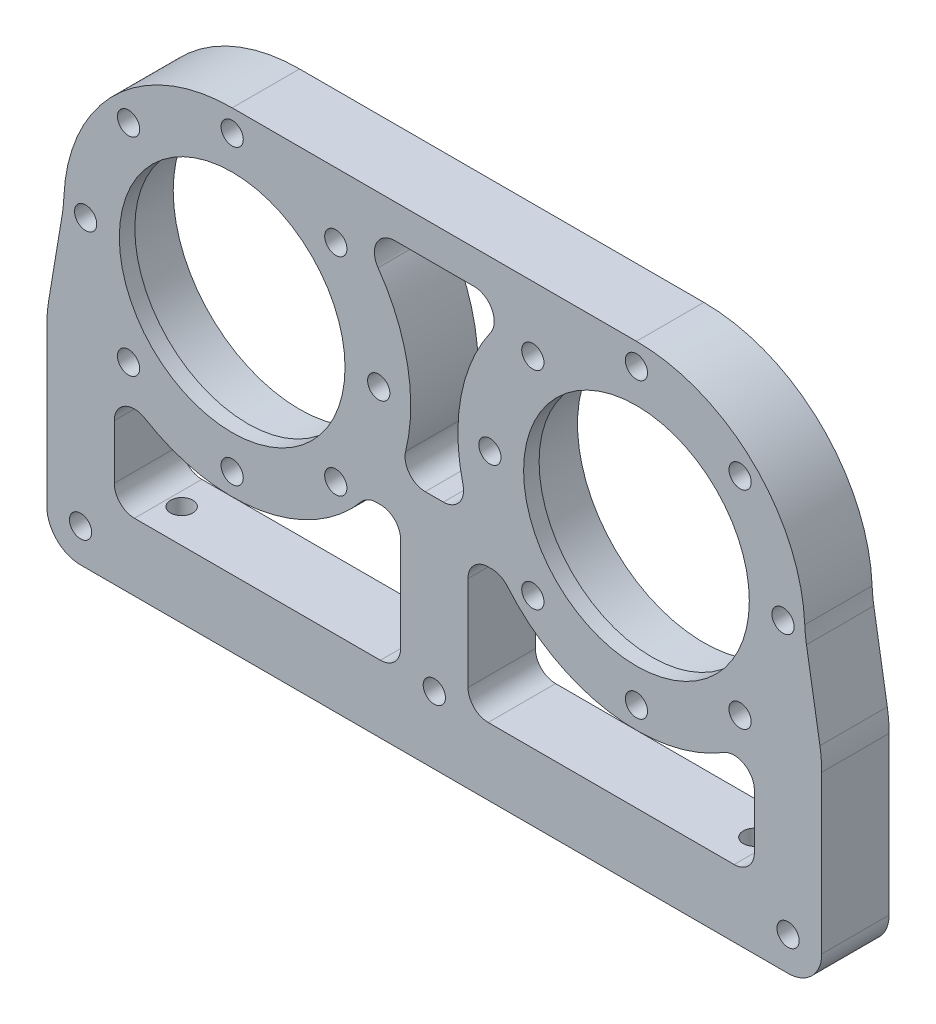
SolidWorks part; units mm, degrees
material "5052-H34"
ref_plane "正面" through (0, 0, 0) normal (0, 0, 1) x (1, 0, 0)
ref_plane "平面" through (0, 0, 0) normal (0, 1, 0) x (1, 0, 0)
ref_plane "右側面" through (0, 0, 0) normal (1, 0, 0) x (0, 0, -1)
sketch "ｽｹｯﾁ1" plane through (0, 0, 0) normal (0, 0, 1) x (1, 0, 0)
  line L0 (-57.5, 15) -> (-2.5, 15) construction
  line L1 (57.5, 15) -> (-57.5, 15)
  line L2 (57.5, 15) -> (57.5, -15)
  line L3 (57.5, -15) -> (-57.5, -15)
  line L4 (-57.5, 15) -> (-57.5, -15)
  line L5 (57.5, 15) -> (-57.5, -15) construction
  line L6 (57.5, -15) -> (-57.5, 15) construction
  line L7 (0, 15) -> (0, -15) construction
  line L8 (-57.5, 0) -> (57.5, 0) construction
  line L9 (-30, -15) -> (-30, 30) construction
  line L10 (-55, 30) -> (-57.5, 15)
  line L11 (-30, 55) -> (30, 55)
  line L12 (55, 30) -> (57.5, 15)
  circle A0 centre (-30, 30) radius 25
  circle A1 centre (30, 30) radius 25
  point P0 (0, 0)
  point P11 (2.5, 15)
  dimension "D4" = 50
  dimension "D1" = 115
  dimension "D2" = 30
  dimension "D3" = 55
  dimension "D5" = 45
  dimension "D6" = 27.5
extrude "ﾎﾞｽ - 押し出し1" add sketch "ｽｹｯﾁ1" along normal blind 10 contours L1 A1 A0 L4 L3 L2 | A0 L1 | L1 A1 L11 A0 | A1 L1 | A1 L1 | L1 A0 | L12 A1 L1 | A0 L10 L1
fillet "ﾌｨﾚｯﾄ1" radius 20 4 edges at (-57.5, 15, 5) (-55, 30, 5) (55, 30, 5) (57.5, 15, 5)
sketch "ｽｹｯﾁ2" plane through (0, 0, 10) normal (0, 0, 1) x (1, 0, 0)
  line L0 (0, 0) -> (0, 55) construction
  line L1 (-30, 55) -> (30, 55) construction
  line L2 (30, 30) -> (30, -15) construction
  line L3 (57.5, -15) -> (-57.5, -15) construction
  circle A0 centre (30, 30) radius 18.75
  circle A1 centre (-30, 30) radius 18.75
  dimension "D1" = 37.5
extrude "ｶｯﾄ - 押し出し1" cut sketch "ｽｹｯﾁ2" against normal through all
sketch "ｽｹｯﾁ4" plane through (0, 0, 0) normal (0, 0, -1) x (-1, 0, 0)
  line L0 (-57.5, -15) -> (57.5, -15) construction
  line L1 (-47.5, 15) -> (47.5, 15)
  line L2 (-47.5, 15) -> (-47.5, -5)
  line L3 (-47.5, -5) -> (47.5, -5)
  line L4 (47.5, 15) -> (47.5, -5)
  line L5 (-57.5, 13.3447) -> (-57.5, -15) construction
  line L6 (57.5, 13.3447) -> (57.5, -15) construction
  line L7 (0, 15) -> (0, -5) construction
  line L9 (-5, 15) -> (5, 15)
  line L10 (-5, 15) -> (-5, -5)
  line L11 (-5, -5) -> (5, -5)
  line L12 (5, 15) -> (5, -5)
  circle A0 centre (-30, 30) radius 25
  circle A1 centre (30, 30) radius 25
  dimension "D5" = 50
  dimension "D1" = 10
  dimension "D2" = 10
  dimension "D3" = 10
  dimension "D4" = 20
  dimension "D6" = 5
  dimension "D7" = 5
extrude "ｶｯﾄ - 押し出し3" cut sketch "ｽｹｯﾁ4" against normal through all contours A0 L1 L2 L3 L10 | L1 A1 L12 L3 L4
fillet "ﾌｨﾚｯﾄ3" radius 3 10 edges at (10, 15, 5) (5, 15, 5) (5, -5, 5) (47.5, -5, 5) (-47.5, -5, 5) (-5, -5, 5) (-5, 15, 5) (-10, 15, 5) (-47.5, 12.1464, 5) (47.5, 12.1464, 5)
sketch "ｽｹｯﾁ5" plane through (0, 0, 0) normal (0, 0, -1) x (-1, 0, 0)
  line L0 (0, 0) -> (0, 55) construction
  line L1 (30, 55) -> (-30, 55) construction
  line L2 (-30, 48.75) -> (-30, 11.25) construction
  circle A0 centre (-30, 30) radius 21.75 construction
  circle A1 centre (-30, 51.75) radius 1.65
  circle A2 centre (-14.6204, 45.3796) radius 1.65
  circle A3 centre (-8.25, 30) radius 1.65
  circle A4 centre (-14.6204, 14.6204) radius 1.65
  circle A5 centre (-30, 8.25) radius 1.65
  circle A6 centre (-45.3796, 14.6204) radius 1.65
  circle A7 centre (-51.75, 30) radius 1.65
  circle A8 centre (-45.3796, 45.3796) radius 1.65
  circle A9 centre (30, 30) radius 21.75 construction
  circle A10 centre (45.3796, 45.3796) radius 1.65
  circle A11 centre (51.75, 30) radius 1.65
  circle A12 centre (45.3796, 14.6204) radius 1.65
  circle A13 centre (30, 8.25) radius 1.65
  circle A14 centre (14.6204, 14.6204) radius 1.65
  circle A15 centre (8.25, 30) radius 1.65
  circle A16 centre (14.6204, 45.3796) radius 1.65
  circle A17 centre (30, 51.75) radius 1.65
  circle A18 centre (-30, 30) radius 18.75 construction
  point P22 (-30, 30)
  point P43 (30, 30)
  dimension "D1" = 43.5
  dimension "D2" = 3.3
  dimension "D3" = 8
extrude "ｶｯﾄ - 押し出し4" cut sketch "ｽｹｯﾁ5" against normal through all
sketch "ｽｹｯﾁ6" plane through (0, 0, 0) normal (0, 0, -1) x (-1, 0, 0)
  line L0 (-57.5, -15) -> (57.5, -15) construction
  line L1 (-57.5, 13.3447) -> (-57.5, -15) construction
  line L2 (0, 0) -> (0, -15) construction
  circle A0 centre (-52.5, -10) radius 1.65
  circle A1 centre (52.5, -10) radius 1.65
  circle A2 centre (0, -5) radius 1.65
  dimension "D1" = 3.3
  dimension "D2" = 5
  dimension "D3" = 5
  dimension "D4" = 10
  dimension "D5" = 3.3
extrude "ｶｯﾄ - 押し出し5" cut sketch "ｽｹｯﾁ6" against normal through all
fillet "ﾌｨﾚｯﾄ5" radius 5 2 edges at (-57.5, -15, 5) (57.5, -15, 5)
sketch "ｽｹｯﾁ7" plane through (0, 0, 10) normal (0, 0, 1) x (1, 0, 0)
  circle A0 centre (-30, 30) radius 18.75
  circle A1 centre (30, 30) radius 18.75
  circle A2 centre (-30, 30) radius 16.75
  circle A3 centre (30, 30) radius 16.75
  dimension "D1" = 37.5
  dimension "D2" = 37.5
  dimension "D3" = 33.5
  dimension "D4" = 33.5
extrude "ﾎﾞｽ - 押し出し2" add sketch "ｽｹｯﾁ7" against normal blind 2.3
sketch "ｽｹｯﾁ8" plane through (0, 0, 0) normal (0, 0, -1) x (-1, 0, 0)
  line L0 (0, 0) -> (0, 55) construction
  line L1 (30, 55) -> (-30, 55) construction
  line L2 (-12.6147, 50) -> (12.6147, 50)
  line L3 (-5.4592, 20) -> (5.4592, 20)
  line L4 (-52.5, -15) -> (52.5, -15) construction
  circle A0 centre (-30, 30) radius 26.5
  circle A1 centre (30, 30) radius 26.5
  point P15 (0, 20)
  point P16 (0, 50)
  dimension "D1" = 53
  dimension "D2" = 5
  dimension "D3" = 35
extrude "ｶｯﾄ - 押し出し6" cut sketch "ｽｹｯﾁ8" against normal blind 10 contours L3 L0 L2 A0 | L0 L3 A1 L2
fillet "ﾌｨﾚｯﾄ6" radius 3 4 edges at (-5.4592, 20, 5) (5.4592, 20, 5) (-12.6147, 50, 5) (12.6147, 50, 5)
sketch "ｽｹｯﾁ9" plane through (0, -15, 0) normal (0, -1, 0) x (1, 0, 0)
  line L0 (-57.5, 5) -> (57.5, 5) construction
  line L1 (-57.5, 0) -> (-57.5, 10) construction
  line L2 (57.5, 10) -> (57.5, 0) construction
  line L3 (0, 5) -> (0, 10) construction
  line L4 (52.5, 10) -> (-52.5, 10) construction
  circle A0 centre (-42.5, 5) radius 1.65
  circle A1 centre (42.5, 5) radius 1.65
  dimension "D1" = 3.3
  dimension "D2" = 15
extrude "ｶｯﾄ - 押し出し7" cut sketch "ｽｹｯﾁ9" against normal blind 10
